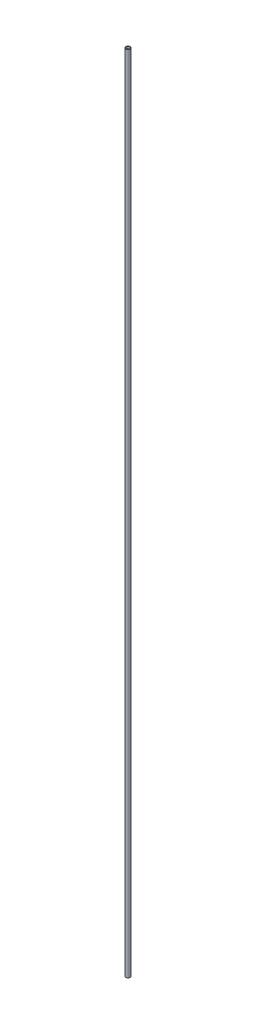
SolidWorks part; units mm, degrees
ref_plane "Front Plane" through (0, 0, 0) normal (0, 0, 1) x (1, 0, 0)
ref_plane "Top Plane" through (0, 0, 0) normal (0, 1, 0) x (1, 0, 0)
ref_plane "Right Plane" through (0, 0, 0) normal (1, 0, 0) x (0, 0, -1)
sketch "Sketch1" plane through (0, 0, 0) normal (0, 1, 0) x (1, 0, 0)
  circle A0 centre (0, 0) radius 4.7625
  circle A1 centre (0, 0) radius 3.7465
  dimension "D1" = 9.525
  dimension "D2" = 1.016
extrude "Boss-Extrude1" add sketch "Sketch1" along normal mid plane 1778
